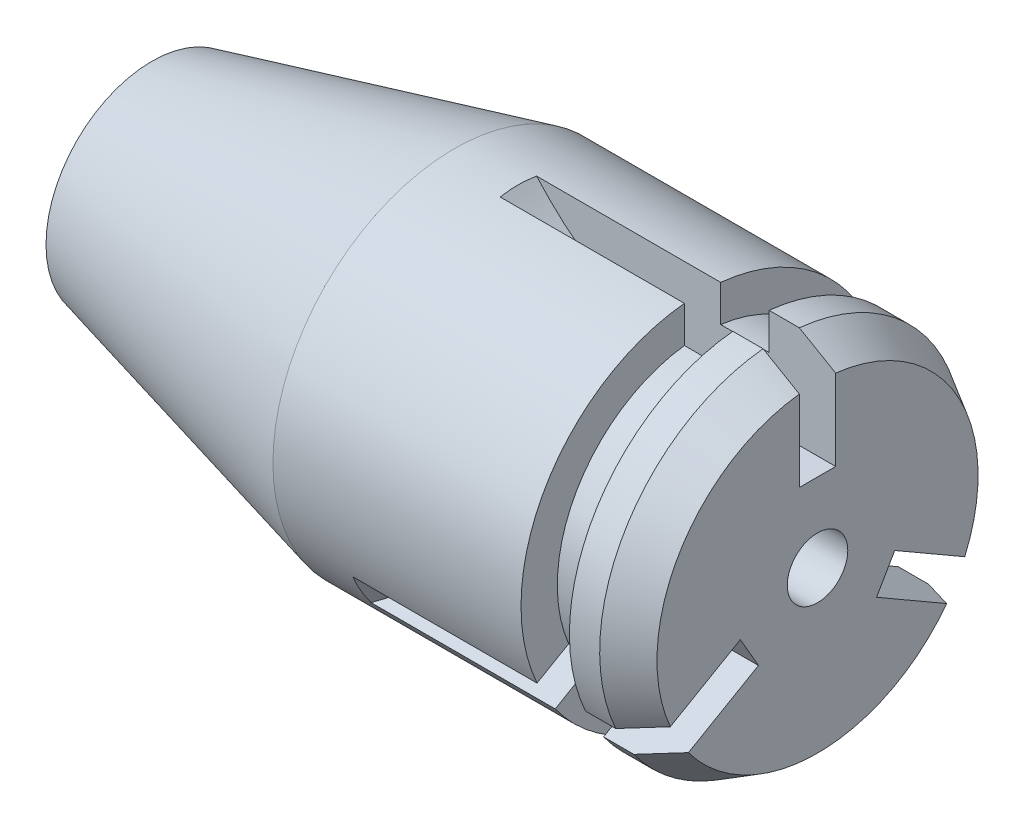
SolidWorks part; units mm, degrees
material "Plain Carbon Steel"
ref_plane "Спереди" through (0, 0, 0) normal (0, 0, 1) x (1, 0, 0)
ref_plane "Сверху" through (0, 0, 0) normal (0, 1, 0) x (1, 0, 0)
ref_plane "Справа" through (0, 0, 0) normal (1, 0, 0) x (0, 0, -1)
sketch "Sketch1" plane through (0, 0, 0) normal (0, 0, 1) x (1, 0, 0)
  line L0 (0, 0) -> (161.9804, 0) construction
  line L1 (0, 13.5) -> (0, 17.5)
  line L2 (0, 17.5) -> (50, 30)
  line L3 (50, 30) -> (91, 30)
  line L4 (91, 30) -> (91, 24)
  line L5 (91, 24) -> (99, 24)
  line L6 (99, 24) -> (99, 30)
  line L7 (99, 30) -> (104, 30)
  line L8 (104, 30) -> (110, 26.5359)
  line L9 (110, 26.5359) -> (110, 0)
  line L10 (110, 0) -> (17.2169, 0)
  line L11 (17.2169, 0) -> (10, 12.5)
  line L12 (10, 12.5) -> (1, 12.5)
  line L13 (1, 12.5) -> (0, 13.5)
  point P3 (0, 12.5)
  dimension "D1" = 35
  dimension "D2" = 25
  dimension "D3" = 60
  dimension "D4" = 110
  dimension "D5" = 8
  dimension "D6" = 60
  dimension "D7" = 11
  dimension "D8" = 6
  dimension "D9" = 30
  dimension "D10" = 6
  dimension "D11" = 50
  dimension "D12" = 10
revolve "Revolve1" add sketch "Sketch1" angle 360 about L0
sketch "Sketch2" plane through (0, 0, 0) normal (0, 0, 1) x (1, 0, 0)
  line L0 (98, 13) -> (110, 13)
  line L1 (110, -26.5359) -> (110, 26.5359) construction
  line L2 (110, 13) -> (110, 30)
  line L3 (110, 30) -> (60.4367, 30)
  line L4 (91, 30) -> (50, 30) construction
  arc A0 (60.4367, 30) -> (98, 13) centre (98, 63) ccw
  dimension "D3" = 100
  dimension "D1" = 13
  dimension "D2" = 12
extrude "Cut-Extrude1" cut sketch "Sketch2" against normal mid plane 6
pattern_circular "CirPattern1" count 3 over 360 about axis through (0, 0, 0) along (1, 0, 0) of "Cut-Extrude1"
hole_wizard "M10 Tapped Hole1" positions "Sketch4" profile "Sketch3" tap size "M10" standard "ISO"
sketch "Sketch4" plane through (110, 0, 0) normal (1, 0, 0) x (0, 0, -1)
  arc A0 (-3, 26.3658) -> (-24.3334, -10.5848) centre (0, 0) ccw construction
  point P0 (0, 0)
sketch "Sketch3" plane through (110, 0, 0) normal (0, 1, 0) x (0, 0, -1)
  line L0 (0, 0) -> (0, 27.0537)
  line L1 (0, 27.0537) -> (4.25, 24.5)
  line L2 (4.25, 24.5) -> (4.25, 20)
  line L3 (4.25, 20) -> (5, 20)
  line L4 (5, 20) -> (5, 0)
  line L5 (5, 0) -> (0, 0)
  line L10 (0, 27.0537) -> (-4.25, 24.5) construction
  line L11 (0, -6.35) -> (0, 107.95) construction
  dimension "Tap Drill Dia." = 8.5
  dimension "Tap Drill Depth" = 24.5
  dimension "Thread Major Dia." = 10
  dimension "Thread Depth" = 20
  dimension "Drill Angle" = 118
